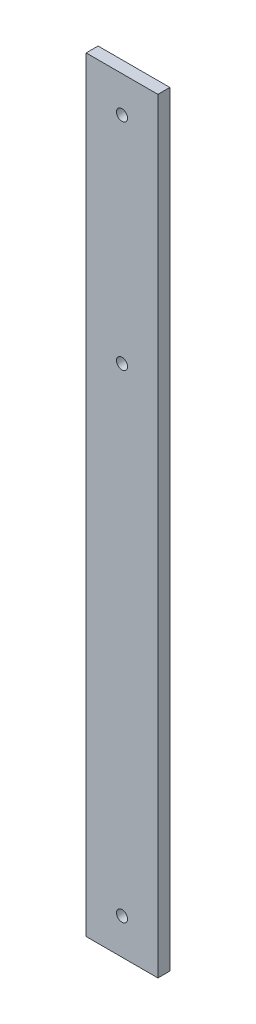
SolidWorks part; units mm, degrees
ref_plane "Front Plane" through (0, 0, 0) normal (0, 0, 1) x (1, 0, 0)
ref_plane "Top Plane" through (0, 0, 0) normal (0, 1, 0) x (1, 0, 0)
ref_plane "Right Plane" through (0, 0, 0) normal (1, 0, 0) x (0, 0, -1)
sketch "Sketch1" plane through (0, 0, 0) normal (0, 0, 1) x (1, 0, 0)
  line L1 (0, 0) -> (19.05, 0)
  line L2 (0, 0) -> (0, 203.2)
  line L3 (0, 203.2) -> (19.05, 203.2)
  line L4 (19.05, 0) -> (19.05, 203.2)
  dimension "D1" = 203.2
  dimension "D2" = 19.05
extrude "Boss-Extrude1" add sketch "Sketch1" along normal blind 3.175
sketch "Sketch4" plane through (0, 0, 3.175) normal (0, 0, 1) x (1, 0, 0)
  line L0 (19.05, 203.2) -> (0, 203.2) construction
  line L2 (0, 0) -> (19.05, 0) construction
  circle A0 centre (9.525, 193.675) radius 1.4605
  circle A1 centre (9.525, 136.525) radius 1.4605
  circle A2 centre (9.525, 9.525) radius 1.4605
  dimension "D1" = 2.921
  dimension "D2" = 2.921
  dimension "D3" = 57.15
  dimension "D4" = 9.525
  dimension "D5" = 9.525
  dimension "D6" = 2.921
extrude "Cut-Extrude1" cut sketch "Sketch4" against normal through all
